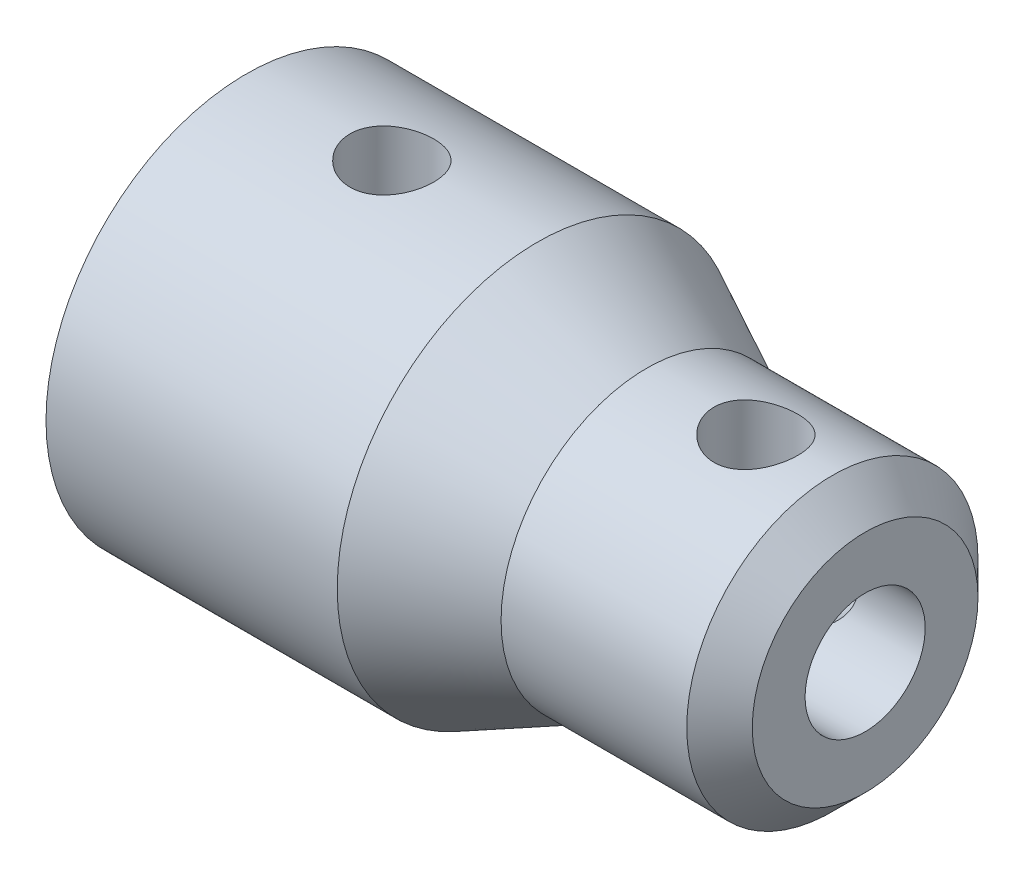
SolidWorks part; units mm, degrees
material "PLA"
ref_plane "Front Plane" through (0, 0, 0) normal (0, 0, 1) x (1, 0, 0)
ref_plane "Top Plane" through (0, 0, 0) normal (0, 1, 0) x (1, 0, 0)
ref_plane "Right Plane" through (0, 0, 0) normal (1, 0, 0) x (0, 0, -1)
sketch "Sketch1" plane through (0, 0, 0) normal (0, 1, 0) x (1, 0, 0)
  line L0 (0, 0) -> (50114.9151, 0) construction
  line L1 (0, -1002.2983) -> (0, 0) construction
  line L2 (-10.16, 3.4036) -> (0, 3.4036)
  line L3 (0, 6.985) -> (3.81, 5.08)
  line L4 (-10.16, 3.4036) -> (-10.16, 6.985)
  line L5 (-10.16, 6.985) -> (0, 6.985)
  line L8 (11.43, 5.08) -> (11.43, 2.0955)
  line L9 (0, 3.4036) -> (0, 50114.9151) construction
  line L10 (0, 3.4036) -> (1.905, 2.0955)
  line L11 (1.905, 2.0955) -> (11.43, 2.0955)
  line L12 (3.81, 5.08) -> (11.43, 5.08)
  line L13 (0.4092, 3.4036) -> (50000.4092, 3.4036) construction
  line L14 (0, 6.985) -> (50000, 6.985) construction
  dimension "D1" = 4.191
  dimension "D2" = 6.8072
  dimension "D3" = 1.905
  dimension "D4" = 13.97
  dimension "D5" = 10.16
  dimension "D6" = 21.59
  dimension "D7" = 10.16
  dimension "D8" = 3.81
revolve "Revolve1" add sketch "Sketch1" angle 360 about L0
sketch "Sketch2" plane through (0, 0, 0) normal (0, 1, 0) x (1, 0, 0)
  line L0 (0, 0) -> (50000, 0) construction
  line L1 (0, 6.985) -> (-10.16, 6.985) construction
  line L2 (-5.08, 6.985) -> (-5.08, 0) construction
  line L3 (7.62, 5.08) -> (7.62, 0) construction
  line L4 (11.43, 5.08) -> (3.81, 5.08) construction
  circle A0 centre (-5.08, 0) radius 1.4605
  circle A1 centre (7.62, 0) radius 1.4605
  dimension "D1" = 2.921
  dimension "D2" = 2.921
extrude "Cut-Extrude1" cut sketch "Sketch2" along normal through all
pattern_circular "CirPattern1" count 2 every 90 about axis through (-10.16, 0, 0) along (-1, 0, 0) of "Cut-Extrude1"
chamfer "Chamfer1" distance 1.143 angle 45 1 edges at (11.43, 0, 5.08)
equation "\"D2@Sketch2\"=\"D1@Sketch2\""
